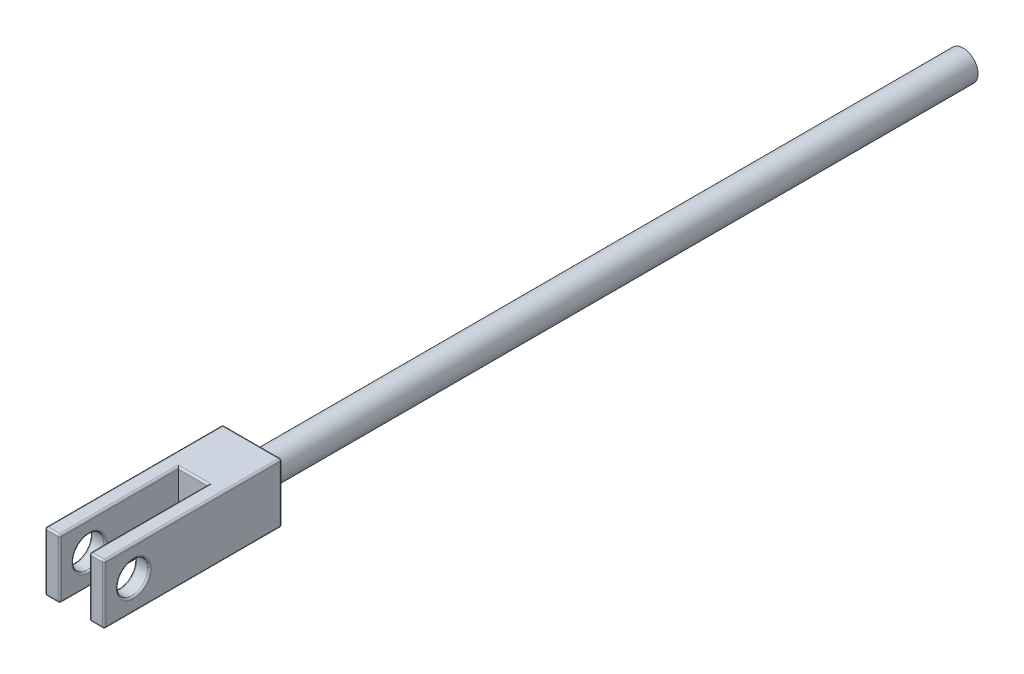
SolidWorks part; units mm, degrees
material "Plain Carbon Steel"
ref_plane "Front" through (0, 0, 0) normal (0, 0, 1) x (1, 0, 0)
ref_plane "Top" through (0, 0, 0) normal (0, 1, 0) x (1, 0, 0)
ref_plane "Right" through (0, 0, 0) normal (1, 0, 0) x (0, 0, -1)
sketch "Sketch1" plane through (0, 0, 0) normal (0, 0, 1) x (1, 0, 0)
  circle A0 centre (0, 0) radius 3.175
  dimension "D1" = 6.35
extrude "Extrude1" add sketch "Sketch1" along normal blind 152.4
sketch "Sketch2" plane through (0, 0, 152.4) normal (0, 0, 1) x (1, 0, 0)
  line L1 (-6.35, -6.35) -> (6.35, -6.35)
  line L2 (-6.35, -6.35) -> (-6.35, 6.35)
  line L3 (-6.35, 6.35) -> (6.35, 6.35)
  line L4 (6.35, -6.35) -> (6.35, 6.35)
  line L5 (-6.35, -6.35) -> (6.35, 6.35) construction
  line L6 (-6.35, 6.35) -> (6.35, -6.35) construction
  point P0 (0, 0)
  dimension "D1" = 12.7
extrude "Extrude2" add sketch "Sketch2" along normal blind 38.1
sketch "Sketch3" plane through (0, 6.35, 0) normal (0, 1, 0) x (1, 0, 0)
  line L0 (6.35, -190.5) -> (-6.35, -190.5) construction
  line L1 (-3.175, -190.5) -> (3.175, -190.5)
  line L2 (-3.175, -190.5) -> (-3.175, -165.1)
  line L3 (-3.175, -165.1) -> (3.175, -165.1)
  line L4 (3.175, -190.5) -> (3.175, -165.1)
  line L5 (0, -152.4) -> (0, -190.5) construction
  line L6 (6.35, -152.4) -> (-6.35, -152.4) construction
  line L7 (6.35, -190.5) -> (6.35, -152.4) construction
  dimension "D1" = 3.175
  dimension "D2" = 12.7
extrude "Extrude3" cut sketch "Sketch3" against normal through all
hole_wizard "1/4 Clearance Hole1" positions "Sketch5" profile "Sketch4" hole size "1/4" standard "Ansi Inch" end condition through all
sketch "Sketch5" plane through (6.35, 0, 0) normal (1, 0, 0) x (0, 0, -1)
  line L0 (-184.15, 6.35) -> (-184.15, -6.35) construction
  line L1 (-190.5, 6.35) -> (-152.4, 6.35) construction
  line L2 (-190.5, -6.35) -> (-152.4, -6.35) construction
  line L4 (-190.5, -6.35) -> (-190.5, 6.35) construction
  point P0 (-184.15, 0)
  dimension "D1" = 6.35
sketch "Sketch4" plane through (6.35, 0, 184.15) normal (0, 1, 0) x (0, 0, -1)
  line L0 (0, 0) -> (0, 12.7)
  line L1 (0, 12.7) -> (3.3782, 12.7)
  line L2 (3.3782, 12.7) -> (3.3782, 0)
  line L5 (3.3782, 0) -> (0, 0)
  line L11 (0, -6.35) -> (0, 107.95) construction
  dimension "Thru Hole Dia." = 6.7564
  dimension "Thru Hole Depth" = 12.7
fillet "Fillet1" radius 0.381 27 edges at (-3.175, 0, 187.5282) (-6.35, 0, 180.7718) (3.175, 0, 180.7718) (6.35, 0, 180.7718) (3.175, 0, 152.4) (-6.35, 0, 152.4) (6.35, 0, 152.4) (6.35, 0, 190.5) (3.175, 0, 190.5) (-6.35, 0, 190.5) (-3.175, 0, 190.5) (3.175, -6.35, 177.8) (4.7625, -6.35, 190.5) (6.35, -6.35, 171.45) (0, -6.35, 152.4) (-6.35, -6.35, 171.45) (-4.7625, -6.35, 190.5) (-3.175, -6.35, 177.8) (0, -6.35, 165.1) (-6.35, 6.35, 171.45) (0, 6.35, 152.4) (6.35, 6.35, 171.45) (4.7625, 6.35, 190.5) (3.175, 6.35, 177.8) (0, 6.35, 165.1) (-3.175, 6.35, 177.8) (-4.7625, 6.35, 190.5)
